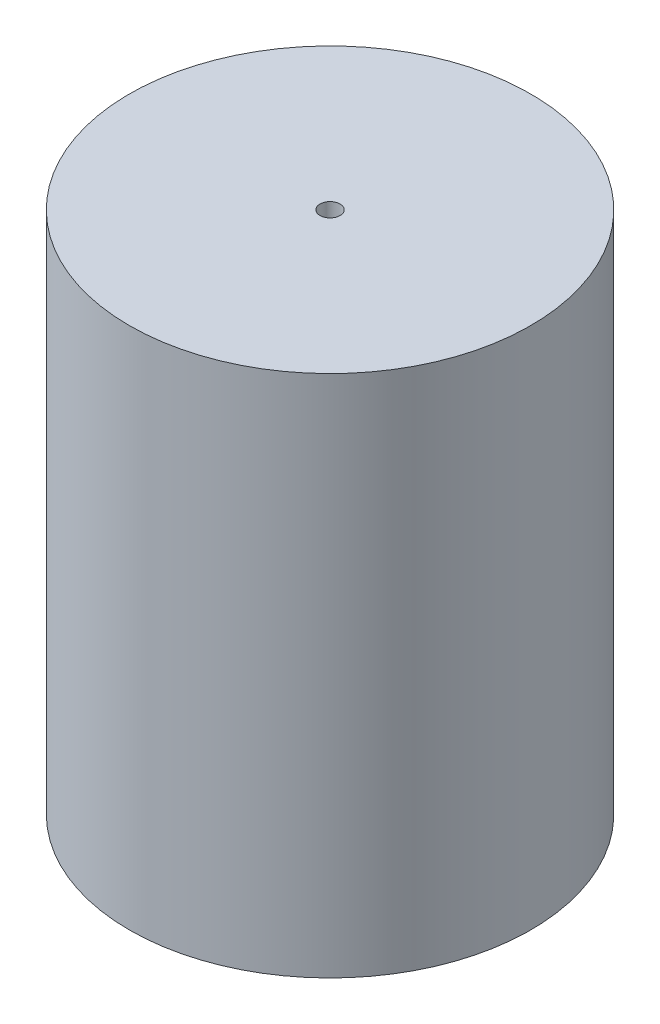
SolidWorks part; units mm, degrees
ref_plane "Front Plane" through (0, 0, 0) normal (0, 0, 1) x (1, 0, 0)
ref_plane "Top Plane" through (0, 0, 0) normal (0, 1, 0) x (1, 0, 0)
ref_plane "Right Plane" through (0, 0, 0) normal (1, 0, 0) x (0, 0, -1)
sketch "Sketch1" plane through (0, 0, 0) normal (0, 1, 0) x (1, 0, 0)
  circle A0 centre (0, 0) radius 23
  dimension "D1" = 46
extrude "Boss-Extrude1" add sketch "Sketch1" along normal blind 60
sketch "Sketch2" plane through (0, 0, 0) normal (0, -1, 0) x (1, 0, 0)
  circle A0 centre (0, 0) radius 20
  dimension "D1" = 40
extrude "Cut-Extrude1" cut sketch "Sketch2" against normal blind 48
sketch "Sketch3" plane through (0, 60, 0) normal (0, 1, 0) x (1, 0, 0)
  circle A0 centre (0, 0) radius 1.15
  dimension "D1" = 2.3
extrude "Cut-Extrude2" cut sketch "Sketch3" against normal blind 50
